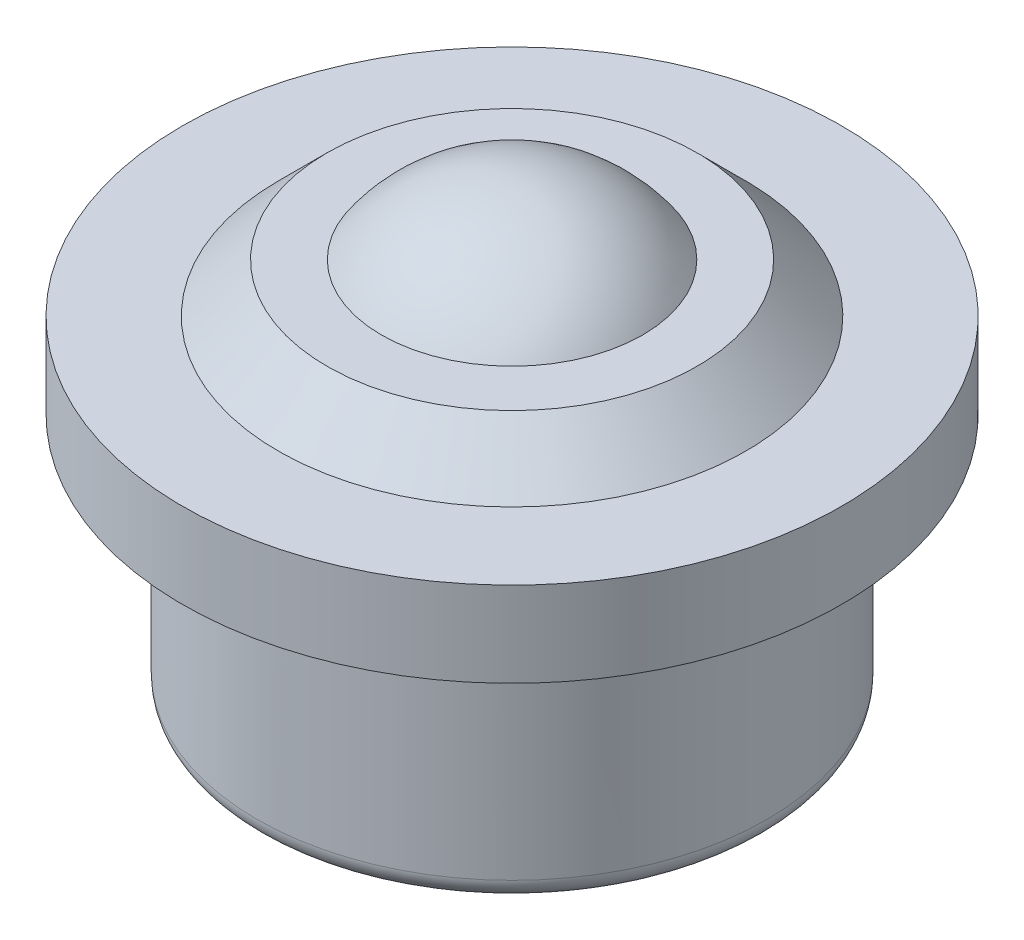
SolidWorks part; units mm, degrees
ref_plane "Plan de face" through (0, 0, 0) normal (0, 0, 1) x (1, 0, 0)
ref_plane "Plan de dessus" through (0, 0, 0) normal (0, 1, 0) x (1, 0, 0)
ref_plane "Plan de droite" through (0, 0, 0) normal (1, 0, 0) x (0, 0, -1)
sketch "Esquisse1" plane through (0, 0, 0) normal (0, 0, 1) x (1, 0, 0)
  line L0 (-10, -13.5) -> (0, -13.5) construction
  line L1 (-12, -2) -> (-15.5, -2)
  line L2 (-11, 2) -> (-15.5, 2)
  line L3 (-6.1449, 4.3) -> (-8.7, 4.3)
  line L4 (-15.5, 2) -> (-15.5, -2)
  line L5 (-12, -2) -> (-12, -12)
  line L6 (0, 7.5) -> (0, -13.5)
  line L7 (-8.7, 4.3) -> (-11, 2)
  line L8 (0, -13.5) -> (-12, -13.5)
  line L9 (-12, -13.5) -> (-12, -12)
  arc A0 (0, 7.5) -> (-6.1449, 4.3) centre (0, 0) ccw
  point P5 (-13.75, -2)
  dimension "D1" = 15
  dimension "D2" = 11.5
  dimension "D5" = 21
  dimension "D12" = 7.5
  dimension "D3" = 6.3
  dimension "D4" = 4
  dimension "D6" = 15.5
  dimension "D7" = 12
  dimension "D8" = 1
  dimension "D11" = 45
revolve "Révolution1" add sketch "Esquisse1" angle 360 about L6
fillet "Fillet1" radius 1 1 edges at (-12, -13.5, 0)
